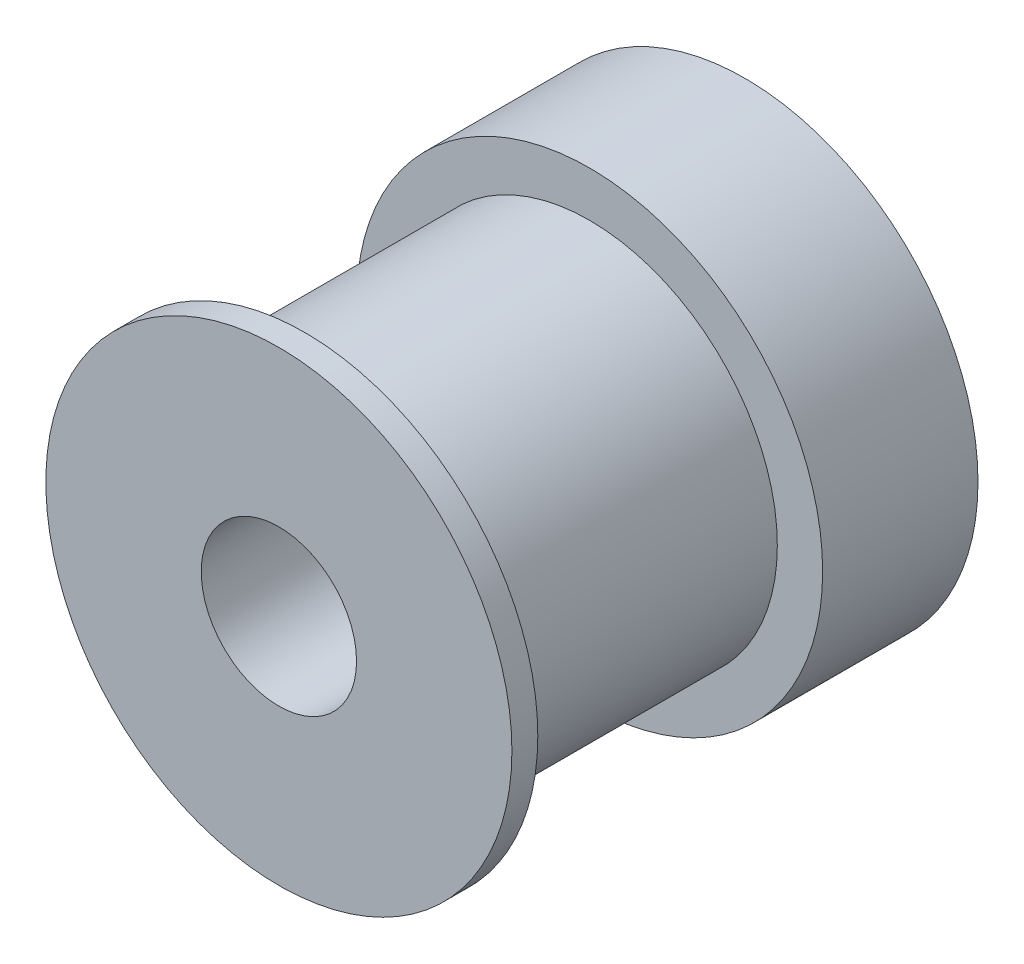
SolidWorks part; units mm, degrees
ref_plane "Front Plane" through (0, 0, 0) normal (0, 0, 1) x (1, 0, 0)
ref_plane "Top Plane" through (0, 0, 0) normal (0, 1, 0) x (1, 0, 0)
ref_plane "Right Plane" through (0, 0, 0) normal (1, 0, 0) x (0, 0, -1)
sketch "Sketch1" plane through (0, 0, 0) normal (0, 0, 1) x (1, 0, 0)
  circle A0 centre (0, 0) radius 3
  circle A1 centre (0, 0) radius 9
  dimension "D1" = 6
  dimension "D2" = 18
extrude "Boss-Extrude1" add sketch "Sketch1" along normal blind 6
sketch "Sketch2" plane through (0, 0, 6) normal (0, 0, 1) x (1, 0, 0)
  circle A0 centre (0, 0) radius 3
  circle A1 centre (0, 0) radius 7.25
  circle A2 centre (0, 0) radius 3 construction
  dimension "D1" = 14.5
extrude "Boss-Extrude2" add sketch "Sketch2" along normal blind 11
sketch "Sketch3" plane through (0, 0, 17) normal (0, 0, 1) x (1, 0, 0)
  circle A0 centre (0, 0) radius 3
  circle A1 centre (0, 0) radius 9
  circle A2 centre (0, 0) radius 3 construction
  dimension "D1" = 18
extrude "Boss-Extrude3" add sketch "Sketch3" along normal blind 1
sketch "Sketch4" plane through (0, 0, 0) normal (0, 1, 0) x (1, 0, 0)
  circle A0 centre (0, -4) radius 1.5
  point P2 (0, 0)
  dimension "D2" = 3
  dimension "D1" = 4
extrude "Cut-Extrude1" cut sketch "Sketch4" against normal through all
